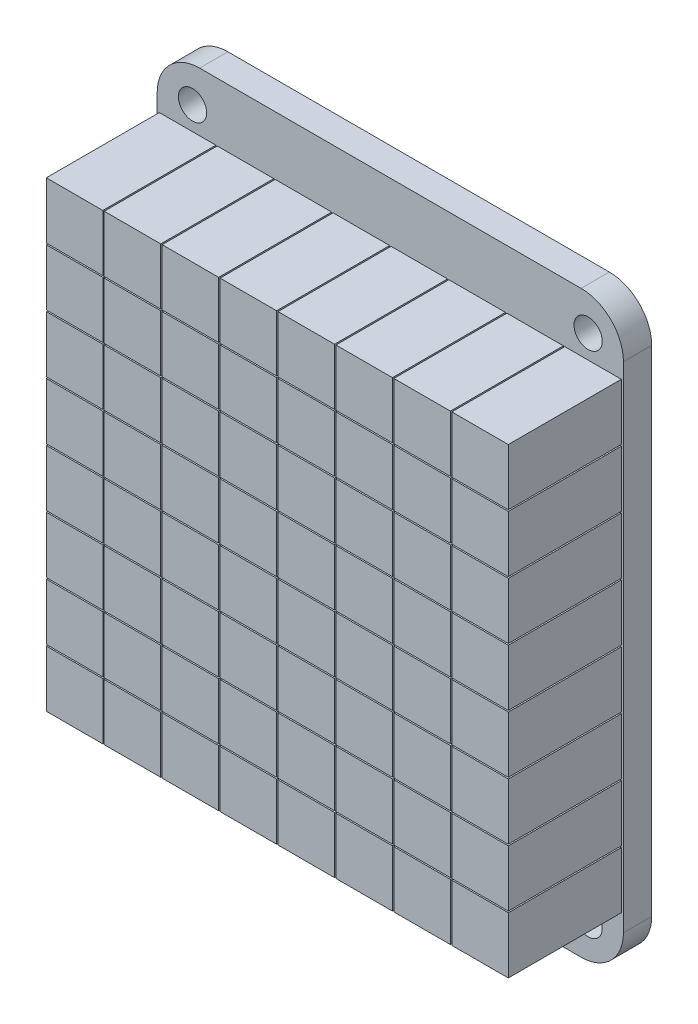
SolidWorks part; units mm, degrees
ref_plane "Front Plane" through (0, 0, 0) normal (0, 0, 1) x (1, 0, 0)
ref_plane "Top Plane" through (0, 0, 0) normal (0, 1, 0) x (1, 0, 0)
ref_plane "Right Plane" through (0, 0, 0) normal (1, 0, 0) x (0, 0, -1)
sketch "Sketch1" plane through (0, 0, 0) normal (0, 0, 1) x (1, 0, 0)
  line L1 (0, 0) -> (33, 0)
  line L2 (0, 0) -> (0, 41)
  line L3 (0, 41) -> (33, 41)
  line L4 (33, 0) -> (33, 41)
  dimension "D1" = 41
  dimension "D2" = 33
extrude "Boss-Extrude1" add sketch "Sketch1" along normal blind 2
sketch "Sketch5" plane through (0, 0, 2) normal (0, 0, 1) x (1, 0, 0)
  line L0 (4.25, 36.85) -> (8.25, 36.85)
  line L1 (0.15, 36.85) -> (4.15, 36.85)
  line L2 (0.15, 36.85) -> (0.15, 32.85)
  line L3 (0.15, 32.85) -> (4.15, 32.85)
  line L4 (4.15, 36.85) -> (4.15, 32.85)
  line L5 (0.15, 36.85) -> (4.15, 32.85) construction
  line L6 (0.15, 32.85) -> (4.15, 36.85) construction
  line L7 (8.25, 36.85) -> (8.25, 32.85)
  line L8 (4.25, 36.85) -> (4.25, 32.85)
  line L9 (4.25, 32.85) -> (8.25, 32.85)
  line L10 (8.35, 36.85) -> (12.35, 36.85)
  line L11 (12.35, 36.85) -> (12.35, 32.85)
  line L12 (8.35, 36.85) -> (8.35, 32.85)
  line L13 (8.35, 32.85) -> (12.35, 32.85)
  line L14 (12.45, 36.85) -> (16.45, 36.85)
  line L15 (16.45, 36.85) -> (16.45, 32.85)
  line L16 (12.45, 36.85) -> (12.45, 32.85)
  line L17 (12.45, 32.85) -> (16.45, 32.85)
  line L18 (16.55, 36.85) -> (20.55, 36.85)
  line L19 (20.55, 36.85) -> (20.55, 32.85)
  line L20 (16.55, 36.85) -> (16.55, 32.85)
  line L21 (16.55, 32.85) -> (20.55, 32.85)
  line L22 (20.65, 36.85) -> (24.65, 36.85)
  line L23 (24.65, 36.85) -> (24.65, 32.85)
  line L24 (20.65, 36.85) -> (20.65, 32.85)
  line L25 (20.65, 32.85) -> (24.65, 32.85)
  line L26 (24.75, 36.85) -> (28.75, 36.85)
  line L27 (28.75, 36.85) -> (28.75, 32.85)
  line L28 (24.75, 36.85) -> (24.75, 32.85)
  line L29 (24.75, 32.85) -> (28.75, 32.85)
  line L30 (28.85, 36.85) -> (32.85, 36.85)
  line L31 (32.85, 36.85) -> (32.85, 32.85)
  line L32 (28.85, 36.85) -> (28.85, 32.85)
  line L33 (28.85, 32.85) -> (32.85, 32.85)
  line L34 (4.25, 32.75) -> (8.25, 32.75)
  line L35 (8.25, 32.75) -> (8.25, 28.75)
  line L36 (4.25, 32.75) -> (4.25, 28.75)
  line L37 (4.25, 28.75) -> (8.25, 28.75)
  line L38 (8.35, 32.75) -> (12.35, 32.75)
  line L39 (12.35, 32.75) -> (12.35, 28.75)
  line L40 (8.35, 32.75) -> (8.35, 28.75)
  line L41 (8.35, 28.75) -> (12.35, 28.75)
  line L42 (12.45, 32.75) -> (16.45, 32.75)
  line L43 (16.45, 32.75) -> (16.45, 28.75)
  line L44 (12.45, 32.75) -> (12.45, 28.75)
  line L45 (12.45, 28.75) -> (16.45, 28.75)
  line L46 (16.55, 32.75) -> (20.55, 32.75)
  line L47 (20.55, 32.75) -> (20.55, 28.75)
  line L48 (16.55, 32.75) -> (16.55, 28.75)
  line L49 (16.55, 28.75) -> (20.55, 28.75)
  line L50 (20.65, 32.75) -> (24.65, 32.75)
  line L51 (24.65, 32.75) -> (24.65, 28.75)
  line L52 (20.65, 32.75) -> (20.65, 28.75)
  line L53 (20.65, 28.75) -> (24.65, 28.75)
  line L54 (24.75, 32.75) -> (28.75, 32.75)
  line L55 (28.75, 32.75) -> (28.75, 28.75)
  line L56 (24.75, 32.75) -> (24.75, 28.75)
  line L57 (24.75, 28.75) -> (28.75, 28.75)
  line L58 (28.85, 32.75) -> (32.85, 32.75)
  line L59 (32.85, 32.75) -> (32.85, 28.75)
  line L60 (28.85, 32.75) -> (28.85, 28.75)
  line L61 (28.85, 28.75) -> (32.85, 28.75)
  line L62 (4.25, 28.65) -> (8.25, 28.65)
  line L63 (8.25, 28.65) -> (8.25, 24.65)
  line L64 (4.25, 28.65) -> (4.25, 24.65)
  line L65 (4.25, 24.65) -> (8.25, 24.65)
  line L66 (8.35, 28.65) -> (12.35, 28.65)
  line L67 (12.35, 28.65) -> (12.35, 24.65)
  line L68 (8.35, 28.65) -> (8.35, 24.65)
  line L69 (8.35, 24.65) -> (12.35, 24.65)
  line L70 (12.45, 28.65) -> (16.45, 28.65)
  line L71 (16.45, 28.65) -> (16.45, 24.65)
  line L72 (12.45, 28.65) -> (12.45, 24.65)
  line L73 (12.45, 24.65) -> (16.45, 24.65)
  line L74 (16.55, 28.65) -> (20.55, 28.65)
  line L75 (20.55, 28.65) -> (20.55, 24.65)
  line L76 (16.55, 28.65) -> (16.55, 24.65)
  line L77 (16.55, 24.65) -> (20.55, 24.65)
  line L78 (20.65, 28.65) -> (24.65, 28.65)
  line L79 (24.65, 28.65) -> (24.65, 24.65)
  line L80 (20.65, 28.65) -> (20.65, 24.65)
  line L81 (20.65, 24.65) -> (24.65, 24.65)
  line L82 (24.75, 28.65) -> (28.75, 28.65)
  line L83 (28.75, 28.65) -> (28.75, 24.65)
  line L84 (24.75, 28.65) -> (24.75, 24.65)
  line L85 (24.75, 24.65) -> (28.75, 24.65)
  line L86 (28.85, 28.65) -> (32.85, 28.65)
  line L87 (32.85, 28.65) -> (32.85, 24.65)
  line L88 (28.85, 28.65) -> (28.85, 24.65)
  line L89 (28.85, 24.65) -> (32.85, 24.65)
  line L90 (4.25, 24.55) -> (8.25, 24.55)
  line L91 (8.25, 24.55) -> (8.25, 20.55)
  line L92 (4.25, 24.55) -> (4.25, 20.55)
  line L93 (4.25, 20.55) -> (8.25, 20.55)
  line L94 (8.35, 24.55) -> (12.35, 24.55)
  line L95 (12.35, 24.55) -> (12.35, 20.55)
  line L96 (8.35, 24.55) -> (8.35, 20.55)
  line L97 (8.35, 20.55) -> (12.35, 20.55)
  line L98 (12.45, 24.55) -> (16.45, 24.55)
  line L99 (16.45, 24.55) -> (16.45, 20.55)
  line L100 (12.45, 24.55) -> (12.45, 20.55)
  line L101 (12.45, 20.55) -> (16.45, 20.55)
  line L102 (16.55, 24.55) -> (20.55, 24.55)
  line L103 (20.55, 24.55) -> (20.55, 20.55)
  line L104 (16.55, 24.55) -> (16.55, 20.55)
  line L105 (16.55, 20.55) -> (20.55, 20.55)
  line L106 (20.65, 24.55) -> (24.65, 24.55)
  line L107 (24.65, 24.55) -> (24.65, 20.55)
  line L108 (20.65, 24.55) -> (20.65, 20.55)
  line L109 (20.65, 20.55) -> (24.65, 20.55)
  line L110 (24.75, 24.55) -> (28.75, 24.55)
  line L111 (28.75, 24.55) -> (28.75, 20.55)
  line L112 (24.75, 24.55) -> (24.75, 20.55)
  line L113 (24.75, 20.55) -> (28.75, 20.55)
  line L114 (28.85, 24.55) -> (32.85, 24.55)
  line L115 (32.85, 24.55) -> (32.85, 20.55)
  line L116 (28.85, 24.55) -> (28.85, 20.55)
  line L117 (28.85, 20.55) -> (32.85, 20.55)
  line L118 (4.25, 20.45) -> (8.25, 20.45)
  line L119 (8.25, 20.45) -> (8.25, 16.45)
  line L120 (4.25, 20.45) -> (4.25, 16.45)
  line L121 (4.25, 16.45) -> (8.25, 16.45)
  line L122 (8.35, 20.45) -> (12.35, 20.45)
  line L123 (12.35, 20.45) -> (12.35, 16.45)
  line L124 (8.35, 20.45) -> (8.35, 16.45)
  line L125 (8.35, 16.45) -> (12.35, 16.45)
  line L126 (12.45, 20.45) -> (16.45, 20.45)
  line L127 (16.45, 20.45) -> (16.45, 16.45)
  line L128 (12.45, 20.45) -> (12.45, 16.45)
  line L129 (12.45, 16.45) -> (16.45, 16.45)
  line L130 (16.55, 20.45) -> (20.55, 20.45)
  line L131 (20.55, 20.45) -> (20.55, 16.45)
  line L132 (16.55, 20.45) -> (16.55, 16.45)
  line L133 (16.55, 16.45) -> (20.55, 16.45)
  line L134 (20.65, 20.45) -> (24.65, 20.45)
  line L135 (24.65, 20.45) -> (24.65, 16.45)
  line L136 (20.65, 20.45) -> (20.65, 16.45)
  line L137 (20.65, 16.45) -> (24.65, 16.45)
  line L138 (24.75, 20.45) -> (28.75, 20.45)
  line L139 (28.75, 20.45) -> (28.75, 16.45)
  line L140 (24.75, 20.45) -> (24.75, 16.45)
  line L141 (24.75, 16.45) -> (28.75, 16.45)
  line L142 (28.85, 20.45) -> (32.85, 20.45)
  line L143 (32.85, 20.45) -> (32.85, 16.45)
  line L144 (28.85, 20.45) -> (28.85, 16.45)
  line L145 (28.85, 16.45) -> (32.85, 16.45)
  line L146 (4.25, 16.35) -> (8.25, 16.35)
  line L147 (8.25, 16.35) -> (8.25, 12.35)
  line L148 (4.25, 16.35) -> (4.25, 12.35)
  line L149 (4.25, 12.35) -> (8.25, 12.35)
  line L150 (8.35, 16.35) -> (12.35, 16.35)
  line L151 (12.35, 16.35) -> (12.35, 12.35)
  line L152 (8.35, 16.35) -> (8.35, 12.35)
  line L153 (8.35, 12.35) -> (12.35, 12.35)
  line L154 (12.45, 16.35) -> (16.45, 16.35)
  line L155 (16.45, 16.35) -> (16.45, 12.35)
  line L156 (12.45, 16.35) -> (12.45, 12.35)
  line L157 (12.45, 12.35) -> (16.45, 12.35)
  line L158 (16.55, 16.35) -> (20.55, 16.35)
  line L159 (20.55, 16.35) -> (20.55, 12.35)
  line L160 (16.55, 16.35) -> (16.55, 12.35)
  line L161 (16.55, 12.35) -> (20.55, 12.35)
  line L162 (20.65, 16.35) -> (24.65, 16.35)
  line L163 (24.65, 16.35) -> (24.65, 12.35)
  line L164 (20.65, 16.35) -> (20.65, 12.35)
  line L165 (20.65, 12.35) -> (24.65, 12.35)
  line L166 (24.75, 16.35) -> (28.75, 16.35)
  line L167 (28.75, 16.35) -> (28.75, 12.35)
  line L168 (24.75, 16.35) -> (24.75, 12.35)
  line L169 (24.75, 12.35) -> (28.75, 12.35)
  line L170 (28.85, 16.35) -> (32.85, 16.35)
  line L171 (32.85, 16.35) -> (32.85, 12.35)
  line L172 (28.85, 16.35) -> (28.85, 12.35)
  line L173 (28.85, 12.35) -> (32.85, 12.35)
  line L174 (4.25, 12.25) -> (8.25, 12.25)
  line L175 (8.25, 12.25) -> (8.25, 8.25)
  line L176 (4.25, 12.25) -> (4.25, 8.25)
  line L177 (4.25, 8.25) -> (8.25, 8.25)
  line L178 (8.35, 12.25) -> (12.35, 12.25)
  line L179 (12.35, 12.25) -> (12.35, 8.25)
  line L180 (8.35, 12.25) -> (8.35, 8.25)
  line L181 (8.35, 8.25) -> (12.35, 8.25)
  line L182 (12.45, 12.25) -> (16.45, 12.25)
  line L183 (16.45, 12.25) -> (16.45, 8.25)
  line L184 (12.45, 12.25) -> (12.45, 8.25)
  line L185 (12.45, 8.25) -> (16.45, 8.25)
  line L186 (16.55, 12.25) -> (20.55, 12.25)
  line L187 (20.55, 12.25) -> (20.55, 8.25)
  line L188 (16.55, 12.25) -> (16.55, 8.25)
  line L189 (16.55, 8.25) -> (20.55, 8.25)
  line L190 (20.65, 12.25) -> (24.65, 12.25)
  line L191 (24.65, 12.25) -> (24.65, 8.25)
  line L192 (20.65, 12.25) -> (20.65, 8.25)
  line L193 (20.65, 8.25) -> (24.65, 8.25)
  line L194 (24.75, 12.25) -> (28.75, 12.25)
  line L195 (28.75, 12.25) -> (28.75, 8.25)
  line L196 (24.75, 12.25) -> (24.75, 8.25)
  line L197 (24.75, 8.25) -> (28.75, 8.25)
  line L198 (28.85, 12.25) -> (32.85, 12.25)
  line L199 (32.85, 12.25) -> (32.85, 8.25)
  line L200 (28.85, 12.25) -> (28.85, 8.25)
  line L201 (28.85, 8.25) -> (32.85, 8.25)
  line L202 (4.25, 8.15) -> (8.25, 8.15)
  line L203 (8.25, 8.15) -> (8.25, 4.15)
  line L204 (4.25, 8.15) -> (4.25, 4.15)
  line L205 (4.25, 4.15) -> (8.25, 4.15)
  line L206 (8.35, 8.15) -> (12.35, 8.15)
  line L207 (12.35, 8.15) -> (12.35, 4.15)
  line L208 (8.35, 8.15) -> (8.35, 4.15)
  line L209 (8.35, 4.15) -> (12.35, 4.15)
  line L210 (12.45, 8.15) -> (16.45, 8.15)
  line L211 (16.45, 8.15) -> (16.45, 4.15)
  line L212 (12.45, 8.15) -> (12.45, 4.15)
  line L213 (12.45, 4.15) -> (16.45, 4.15)
  line L214 (16.55, 8.15) -> (20.55, 8.15)
  line L215 (20.55, 8.15) -> (20.55, 4.15)
  line L216 (16.55, 8.15) -> (16.55, 4.15)
  line L217 (16.55, 4.15) -> (20.55, 4.15)
  line L218 (20.65, 8.15) -> (24.65, 8.15)
  line L219 (24.65, 8.15) -> (24.65, 4.15)
  line L220 (20.65, 8.15) -> (20.65, 4.15)
  line L221 (20.65, 4.15) -> (24.65, 4.15)
  line L222 (24.75, 8.15) -> (28.75, 8.15)
  line L223 (28.75, 8.15) -> (28.75, 4.15)
  line L224 (24.75, 8.15) -> (24.75, 4.15)
  line L225 (24.75, 4.15) -> (28.75, 4.15)
  line L226 (28.85, 8.15) -> (32.85, 8.15)
  line L227 (32.85, 8.15) -> (32.85, 4.15)
  line L228 (28.85, 8.15) -> (28.85, 4.15)
  line L229 (28.85, 4.15) -> (32.85, 4.15)
  line L230 (0.15, 32.75) -> (4.15, 32.75)
  line L231 (4.15, 32.75) -> (4.15, 28.75)
  line L232 (0.15, 32.75) -> (0.15, 28.75)
  line L233 (0.15, 28.75) -> (4.15, 28.75)
  line L234 (0.15, 28.65) -> (4.15, 28.65)
  line L235 (4.15, 28.65) -> (4.15, 24.65)
  line L236 (0.15, 28.65) -> (0.15, 24.65)
  line L237 (0.15, 24.65) -> (4.15, 24.65)
  line L238 (0.15, 24.55) -> (4.15, 24.55)
  line L239 (4.15, 24.55) -> (4.15, 20.55)
  line L240 (0.15, 24.55) -> (0.15, 20.55)
  line L241 (0.15, 20.55) -> (4.15, 20.55)
  line L242 (0.15, 20.45) -> (4.15, 20.45)
  line L243 (4.15, 20.45) -> (4.15, 16.45)
  line L244 (0.15, 20.45) -> (0.15, 16.45)
  line L245 (0.15, 16.45) -> (4.15, 16.45)
  line L246 (0.15, 16.35) -> (4.15, 16.35)
  line L247 (4.15, 16.35) -> (4.15, 12.35)
  line L248 (0.15, 16.35) -> (0.15, 12.35)
  line L249 (0.15, 12.35) -> (4.15, 12.35)
  line L250 (0.15, 12.25) -> (4.15, 12.25)
  line L251 (4.15, 12.25) -> (4.15, 8.25)
  line L252 (0.15, 12.25) -> (0.15, 8.25)
  line L253 (0.15, 8.25) -> (4.15, 8.25)
  line L254 (0.15, 8.15) -> (4.15, 8.15)
  line L255 (4.15, 8.15) -> (4.15, 4.15)
  line L256 (0.15, 8.15) -> (0.15, 4.15)
  line L257 (0.15, 4.15) -> (4.15, 4.15)
  line L258 (0, 41) -> (0, 0) construction
  line L259 (33, 41) -> (0, 41) construction
  point P4 (2.15, 34.85)
  dimension "D1" = 4
  dimension "D2" = 4
  dimension "D5" = 0.15
  dimension "D6" = 4.15
  dimension "D3" = 8
  dimension "D4" = 8
extrude "Boss-Extrude2" add sketch "Sketch5" along normal blind 8
fillet "Fillet1" radius 3 4 edges at (33, 0, 1) (0, 0, 1) (33, 41, 1) (0, 41, 1)
sketch "Sketch6" plane through (0, 0, 2) normal (0, 0, 1) x (1, 0, 0)
  line L0 (0, 38) -> (0, 3) construction
  line L1 (30, 41) -> (3, 41) construction
  circle A0 centre (2.5, 38.5) radius 1
  circle A1 centre (30.5, 38.5) radius 1
  circle A2 centre (30.5, 2.5) radius 1
  circle A3 centre (2.5, 2.5) radius 1
  dimension "D1" = 2
  dimension "D2" = 2.5
  dimension "D3" = 2.5
  dimension "D4" = 2
  dimension "D5" = 2
extrude "Cut-Extrude2" cut sketch "Sketch6" against normal blind 2
